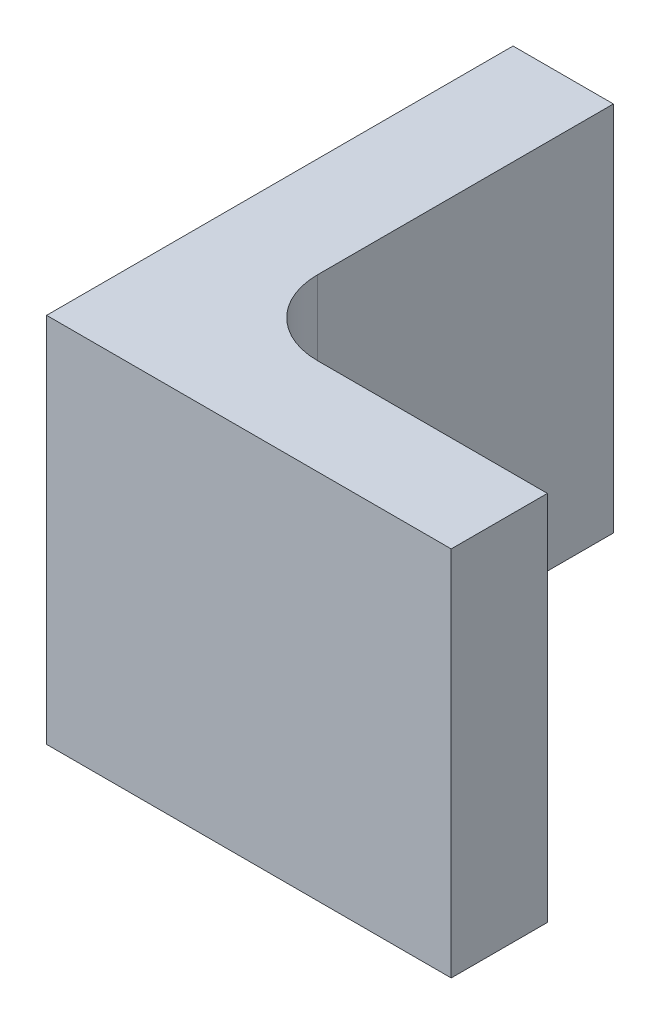
SolidWorks part; units mm, degrees
ref_plane "Front Plane" through (0, 0, 0) normal (0, 0, 1) x (1, 0, 0)
ref_plane "Top Plane" through (0, 0, 0) normal (0, 1, 0) x (1, 0, 0)
ref_plane "Right Plane" through (0, 0, 0) normal (1, 0, 0) x (0, 0, -1)
sketch "Sketch1" plane through (0, 0, 0) normal (0, 1, 0) x (1, 0, 0)
  line L0 (0, 0) -> (54.4409, 0)
  line L1 (54.4409, 0) -> (54.4409, 12.9386)
  line L2 (54.4409, 12.9386) -> (13.501, 12.9386)
  line L3 (13.501, 12.9386) -> (13.501, 62.7616)
  line L4 (13.501, 62.7616) -> (0, 62.7616)
  line L5 (0, 62.7616) -> (0, 0)
extrude "Boss-Extrude1" add sketch "Sketch1" along normal blind 50
fillet "Fillet1" radius 10 1 edges at (13.501, 25, -12.9386)
